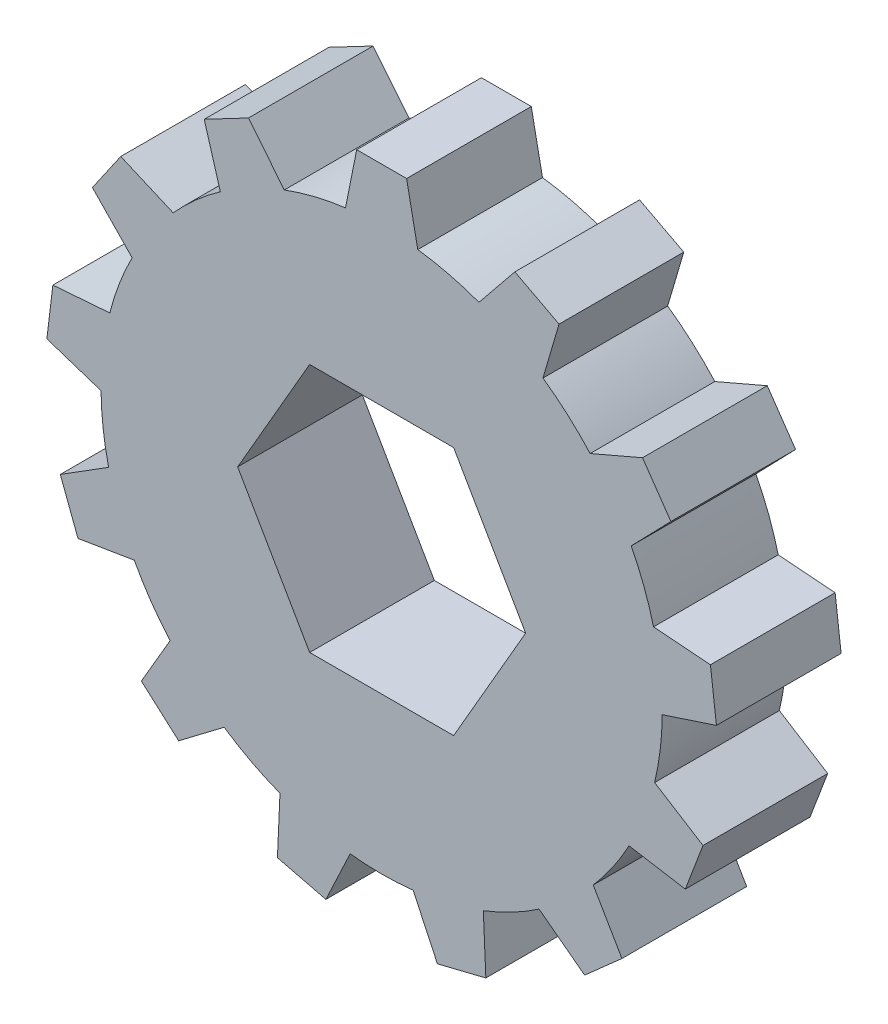
SolidWorks part; units mm, degrees
ref_plane "Front Plane" through (0, 0, 0) normal (0, 0, 1) x (1, 0, 0)
ref_plane "Top Plane" through (0, 0, 0) normal (0, 1, 0) x (1, 0, 0)
ref_plane "Right Plane" through (0, 0, 0) normal (1, 0, 0) x (0, 0, -1)
sketch "Sketch1" plane through (0, 0, 0) normal (0, 0, 1) x (1, 0, 0)
  line L1 (7.3323, 0) -> (3.6662, 6.35)
  line L2 (3.6662, 6.35) -> (-3.6662, 6.35)
  line L3 (-3.6662, 6.35) -> (-7.3323, 0)
  line L4 (-7.3323, 0) -> (-3.6662, -6.35)
  line L5 (-3.6662, -6.35) -> (3.6662, -6.35)
  line L6 (3.6662, -6.35) -> (7.3323, 0)
  circle A0 centre (0, 0) radius 6.35 construction
  circle A1 centre (0, 0) radius 14.2875
  dimension "D1" = 28.575
  dimension "D2" = 12.7
extrude "Boss-Extrude1" add sketch "Sketch1" along normal blind 6.35
sketch "Sketch2" plane through (0, 0, 0) normal (0, 0, 1) x (1, 0, 0)
  line L0 (-1.27, 17.018) -> (1.27, 17.018)
  line L1 (1.27, 17.018) -> (1.905, 13.843)
  line L2 (1.905, 13.843) -> (-1.905, 13.843)
  line L3 (-1.905, 13.843) -> (-1.27, 17.018)
  point P2 (0, 17.018)
  point P6 (0, 13.843)
  dimension "D1" = 17.018
  dimension "D2" = 3.175
  dimension "D3" = 2.54
  dimension "D4" = 3.81
extrude "Boss-Extrude2" add sketch "Sketch2" along normal blind 6.35
pattern_circular "CirPattern1" count 13 over 360 about axis through (0, 0, 0) along (0, 0, 1) of "Boss-Extrude2"
